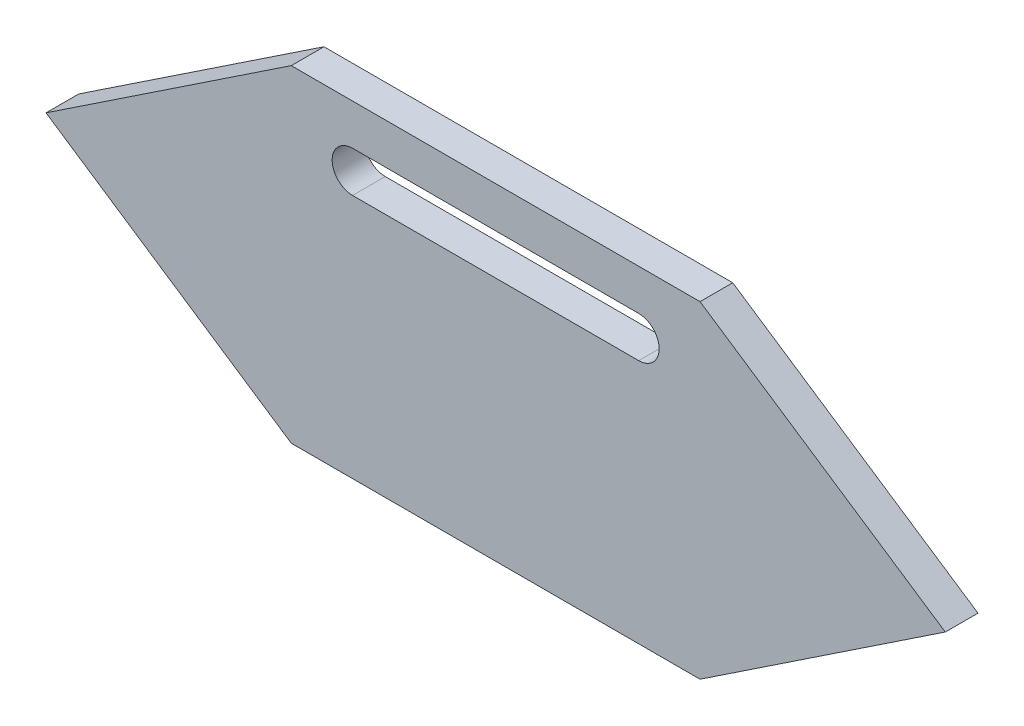
SolidWorks part; units mm, degrees
ref_plane "Front Plane" through (0, 0, 0) normal (0, 0, 1) x (1, 0, 0)
ref_plane "Top Plane" through (0, 0, 0) normal (0, 1, 0) x (1, 0, 0)
ref_plane "Right Plane" through (0, 0, 0) normal (1, 0, 0) x (0, 0, -1)
sketch "Sketch1" plane through (0, 0, 0) normal (0, 0, 1) x (1, 0, 0)
  line L0 (0, -77.6484) -> (0, 84.0788) construction
  line L1 (-63.5, 50.8) -> (63.5, 50.8)
  line L2 (63.5, 50.8) -> (139.7, 0)
  line L3 (139.7, 0) -> (63.5, -50.8)
  line L4 (63.5, -50.8) -> (-63.5, -50.8)
  line L5 (-139.7, 0) -> (-63.5, -50.8)
  line L6 (-44.45, 38.1) -> (44.45, 38.1)
  line L7 (-44.45, 25.4) -> (44.45, 25.4)
  line L8 (-63.5, 50.8) -> (-139.7, 0)
  arc A1 (44.45, 25.4) -> (44.45, 38.1) centre (44.45, 31.75) ccw
  arc A2 (-44.45, 25.4) -> (-44.45, 38.1) centre (-44.45, 31.75) cw
  point P7 (0, 0)
  point P10 (0, 18.1917)
  point P12 (0, 0)
  point P14 (50.8, 31.75)
  point P16 (0, 0)
  point P17 (0, 38.1)
  point P20 (0, 25.4)
  point P21 (0, -50.8)
  point P23 (0, 50.8)
  dimension "D4" = 6.35
  dimension "D1" = 76.2
  dimension "D2" = 101.6
  dimension "D3" = 127
  dimension "D5" = 101.6
  dimension "D6" = 12.7
extrude "Boss-Extrude1" add sketch "Sketch1" along normal mid plane 10.16
